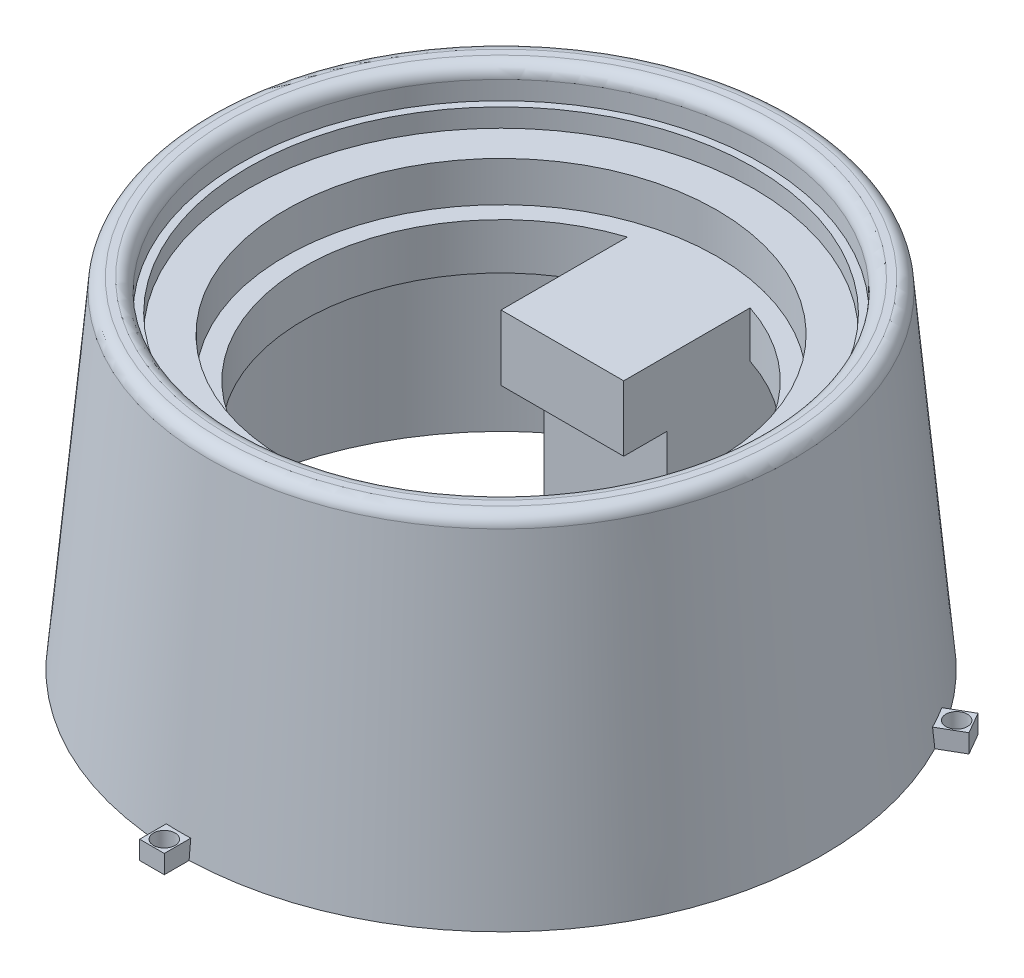
SolidWorks part; units mm, degrees
ref_plane "前视基准面" through (0, 0, 0) normal (0, 0, 1) x (1, 0, 0)
ref_plane "上视基准面" through (0, 0, 0) normal (0, 1, 0) x (1, 0, 0)
ref_plane "右视基准面" through (0, 0, 0) normal (1, 0, 0) x (0, 0, -1)
other "Configuration Table"
sketch "草图1" plane through (0, 0, 0) normal (0, 1, 0) x (1, 0, 0)
  circle A0 centre (0, 0) radius 52.22
  circle A1 centre (0, 0) radius 47.22
  circle A2 centre (0, 0) radius 42.22
  dimension "D1" = 104.44
  dimension "D2" = 94.44
  dimension "D3" = 84.44
extrude "凸台-拉伸1" add sketch "草图1" along normal blind 50 contours A2 | A0 A1 | A1 A2
sketch "草图3" plane through (0, 50, 0) normal (0, 1, 0) x (1, 0, 0)
  circle A1 centre (0, 0) radius 52.22
  circle A2 centre (0, 0) radius 52.22
  circle A3 centre (0, 0) radius 42.22
  circle A4 centre (0, 0) radius 42.22
  circle A5 centre (0, 0) radius 47.22
  circle A6 centre (0, 0) radius 47.22
  circle A7 centre (0, 0) radius 52.22
  circle A8 centre (0, 0) radius 52.22
  circle M5 centre (0, 0) radius 52.22
  dimension "D5" = 94.44
  dimension "D6" = 84.44
  dimension "D1" = 0
  dimension "D2" = 0
  dimension "D3" = 0
  dimension "D4" = 0
extrude "凸台-拉伸2" add sketch "草图3" along normal blind 5 contours A6 M5 | A6 A4
sketch "草图5" plane through (0, 0, 0) normal (1, 0, 0) x (0, 0, -1)
  line L0 (52.22, 55) -> (52.22, 0)
  line L1 (55, 0) -> (-55, 0) construction
  line L2 (52.22, 0) -> (52.22, 55) construction
  line L3 (52.22, 0) -> (47.22, 55)
  line L4 (52.22, 55) -> (-52.22, 55) construction
  line L5 (47.22, 55) -> (52.22, 55)
  line L6 (0, 58.8576) -> (0, -9.8994) construction
revolve "切除-旋转2" cut sketch "草图5" angle 360 about L6
sketch "草图6" plane through (0, 50, 0) normal (0, 1, 0) x (1, 0, 0)
  line L0 (9.95, 9.95) -> (9.95, -30.45)
  line L2 (9.95, 9.95) -> (-9.95, 9.95)
  line L3 (-9.95, 9.95) -> (-9.95, -30.45)
  line L4 (-9.95, -30.45) -> (9.95, -30.45)
extrude "切除-拉伸1" cut sketch "草图6" against normal up to next
sketch "草图8" plane through (0, 50, 0) normal (0, 1, 0) x (1, 0, 0)
  line L0 (-9.95, 9.95) -> (-9.95, 16.95)
  line L1 (9.95, 9.95) -> (9.95, 16.95)
  line L2 (9.95, 16.95) -> (-9.95, 16.95)
  line L3 (-9.95, -30.45) -> (-9.95, -37.45)
  line L4 (9.95, -30.45) -> (9.95, -37.45)
  line L5 (9.95, -37.45) -> (-9.95, -37.45)
  line L6 (-9.95, 9.95) -> (9.95, 9.95)
  line L7 (-9.95, -30.45) -> (9.95, -30.45)
sketch "草图9" plane through (0, 0, 0) normal (0, -1, 0) x (1, 0, 0)
  line L4 (-9.95, 37.45) -> (-9.95, 30.45)
  line L5 (9.95, 37.45) -> (-9.95, 37.45)
  line L6 (9.95, 30.45) -> (9.95, 37.45)
  line L7 (-9.95, 30.45) -> (9.95, 30.45)
  line L8 (-9.95, 37.45) -> (-9.95, 30.45)
  line L9 (9.95, 37.45) -> (-9.95, 37.45)
  line L10 (9.95, 30.45) -> (9.95, 37.45)
  line L11 (-9.95, 30.45) -> (9.95, 30.45)
  line L12 (-9.95, -9.95) -> (-9.95, -16.95)
  line L13 (-9.95, -16.95) -> (9.95, -16.95)
  line L14 (9.95, -16.95) -> (9.95, -9.95)
  line L15 (9.95, -9.95) -> (-9.95, -9.95)
  line L16 (-9.95, -9.95) -> (-9.95, -16.95)
  line L17 (-9.95, -16.95) -> (9.95, -16.95)
  line L18 (9.95, -16.95) -> (9.95, -9.95)
  line L19 (9.95, -9.95) -> (-9.95, -9.95)
  dimension "D1" = 0
  dimension "D2" = 0
extrude "切除-拉伸2" cut sketch "草图9" against normal blind 29.9
sketch "草图10" plane through (0, 29.9, 0) normal (0, -1, 0) x (1, 0, 0)
  line L0 (9.95, 37.45) -> (4.95, 37.45)
  line L1 (9.95, 37.45) -> (-9.95, 37.45) construction
  line L2 (4.95, 37.45) -> (4.95, 34.55)
  line L3 (-9.95, 37.45) -> (-4.95, 37.45)
  line L4 (-4.95, 37.45) -> (-4.95, 34.55)
  line L5 (-9.95, -16.95) -> (-4.95, -16.95)
  line L6 (9.95, -16.95) -> (-9.95, -16.95) construction
  line L7 (-4.95, -16.95) -> (-4.95, -14.05)
  line L8 (9.95, -16.95) -> (4.95, -16.95)
  line L9 (4.95, -16.95) -> (4.95, -14.05)
  circle A0 centre (4.95, 34.55) radius 1.75
  circle A1 centre (-4.95, 34.55) radius 1.75
  circle A2 centre (-4.95, -14.05) radius 1.75
  circle A3 centre (4.95, -14.05) radius 1.75
sketch "草图13" plane through (0, 0, 0) normal (0, 0, 1) x (1, 0, 0)
  line L1 (-5, 0) -> (5, 0)
  line L2 (-52.22, 0) -> (52.22, 0) construction
  line L3 (-5, 0) -> (-5, 10)
  line L4 (-5, 10) -> (5, 10)
  line L5 (5, 10) -> (5, 0)
extrude "切除-拉伸3" cut sketch "草图13" against normal through all
sketch "草图14" plane through (0, 50, 0) normal (0, 1, 0) x (1, 0, 0)
  line L0 (-9.95, -30.45) -> (9.95, -30.45)
  line L1 (9.95, -30.45) -> (9.95, 9.95)
  line L2 (9.95, 9.95) -> (-9.95, 9.95)
  line L3 (-9.95, 9.95) -> (-9.95, -30.45)
  circle A1 centre (0, 0) radius 35
  circle A2 centre (0, 0) radius 42.22
  circle A3 centre (0, 0) radius 42.22
  circle A4 centre (0, 0) radius 41
  dimension "D1" = 0
  dimension "D2" = 84.44
  dimension "D3" = 32.0344
extrude "切除-拉伸4" cut sketch "草图14" against normal blind 3 contours A4 A1
sketch "草图15" plane through (0, 50, 0) normal (0, 1, 0) x (1, 0, 0)
  line L0 (-9.95, 9.95) -> (-9.95, 30.45)
  line L1 (-9.95, 30.45) -> (9.95, 30.45)
  line L2 (9.95, 30.45) -> (9.95, 9.95)
  line L4 (-9.95, -30.45) -> (9.95, -30.45)
  line L5 (9.95, -30.45) -> (9.95, 9.95)
  line L6 (9.95, 9.95) -> (-9.95, 9.95)
  line L7 (-9.95, 9.95) -> (-9.95, -30.45)
  line L8 (-9.95, -30.45) -> (9.95, -30.45)
  line L9 (9.95, -30.45) -> (9.95, 9.95)
  line L10 (9.95, 9.95) -> (-9.95, 9.95)
  line L11 (-9.95, 9.95) -> (-9.95, -30.45)
  circle A0 centre (0, 0) radius 32.0344
  circle A1 centre (0, 0) radius 35
  circle A2 centre (0, 0) radius 35
  circle A3 centre (0, 0) radius 41
  circle A4 centre (0, 0) radius 41
  circle A5 centre (0, 0) radius 42.22
  circle A6 centre (0, 0) radius 42.22
  circle A7 centre (0, 0) radius 35
  circle A8 centre (0, 0) radius 35
  line M11 (9.95, 9.95) -> (9.95, -30.45)
  line M13 (-9.95, -30.45) -> (-9.95, 9.95)
  dimension "D1" = 0
  dimension "D2" = 0
  dimension "D3" = 0
  dimension "D4" = 0
  dimension "D5" = 0
extrude "切除-拉伸5" cut sketch "草图15" against normal through all contours L0 A0 M13 | A0 L2 M11
sketch "草图17" plane through (0, 0, 0) normal (0, -1, 0) x (1, 0, 0)
  line L0 (-9.95, -16.95) -> (-9.95, 46.1598)
  line L1 (-9.95, -16.95) -> (-9.95, -46.1598)
  line L2 (9.95, 37.45) -> (9.95, -46.1598)
  line L3 (9.95, 37.45) -> (9.95, 46.1598)
  circle A1 centre (0, 0) radius 42.22
  circle A2 centre (0, 0) radius 42.22
  circle A3 centre (0, 0) radius 47.22
  circle A4 centre (0, 0) radius 47.22
  circle A5 centre (0, 0) radius 52.22
  circle A6 centre (0, 0) radius 52.22
  arc M6 (-9.95, -30.45) -> (-9.95, 30.45) centre (0, 0) cw
  line M7 (-9.95, 30.45) -> (-9.95, 37.45)
  line M9 (9.95, 37.45) -> (9.95, 30.45)
  arc M10 (9.95, 30.45) -> (9.95, -30.45) centre (0, 0) cw
  dimension "D1" = 0
  dimension "D2" = 0
  dimension "D3" = 0
extrude "切除-拉伸6" cut sketch "草图17" against normal blind 33 contours L0 A2 L1 M6 M7 | L0 A4 L1 A2 | L2 A2 L3 M9 M10 | L2 A4 L3 A2
sketch "草图20" plane through (0, 0, -9.95) normal (0, 0, 1) x (1, 0, 0)
  line L0 (-9.95, 29.9) -> (-9.95, 40.5)
  line L1 (-9.95, 29.9) -> (-4.95, 29.9) construction
  line L2 (-9.95, 40.5) -> (-9.95, 50)
  line L3 (9.95, 50) -> (-9.95, 50) construction
sketch "草图21" plane through (0, 50, 0) normal (0, 1, 0) x (1, 0, 0)
  circle A1 centre (0, 0) radius 35
  circle A2 centre (0, 0) radius 35
  dimension "D1" = 0
extrude "切除-拉伸7" cut sketch "草图21" against normal blind 9.5
sketch "草图22" plane through (0, 0, 0) normal (0, -1, 0) x (1, 0, 0)
  line L0 (0, 0) -> (-0.4162, 52.2183)
  line L1 (0, 0) -> (45.4305, -25.7487)
  line L2 (0, 0) -> (-45.0143, -26.4696)
  line L3 (-0.4162, 52.2183) -> (-0.4162, 56.2183)
  line L4 (-0.4162, 56.2183) -> (-2.4162, 56.2183)
  line L5 (-0.4162, 56.2183) -> (1.5838, 56.2183)
  line L6 (-2.4162, 56.2183) -> (-2.4162, 50.2183)
  line L7 (-2.4162, 50.2183) -> (1.5838, 50.2183)
  line L8 (1.5838, 50.2183) -> (1.5838, 56.2183)
  line L9 (-9.95, 46.1598) -> (-9.95, 37.45)
  line L10 (-9.95, 37.45) -> (9.95, 37.45)
  line L11 (9.95, 37.45) -> (9.95, 46.1598)
  line L12 (9.95, -46.1598) -> (9.95, -16.95)
  line L13 (9.95, -16.95) -> (5, -16.95)
  line L14 (5, -16.95) -> (5, -51.9801)
  line L15 (-5, -51.9801) -> (-5, -16.95)
  line L16 (-5, -16.95) -> (-9.95, -16.95)
  line L17 (-9.95, -16.95) -> (-9.95, -46.1598)
  line L18 (-9.95, 46.1598) -> (-9.95, 37.45)
  line L19 (-9.95, 37.45) -> (9.95, 37.45)
  line L20 (9.95, 37.45) -> (9.95, 46.1598)
  line L21 (9.95, -46.1598) -> (9.95, -16.95)
  line L22 (9.95, -16.95) -> (5, -16.95)
  line L23 (5, -16.95) -> (5, -51.9801)
  line L24 (-5, -51.9801) -> (-5, -16.95)
  line L25 (-5, -16.95) -> (-9.95, -16.95)
  line L26 (-9.95, -16.95) -> (-9.95, -46.1598)
  line L27 (48.8946, -27.7487) -> (49.8946, -26.0167)
  line L28 (48.8946, -27.7487) -> (47.8946, -29.4808)
  line L29 (49.8946, -26.0167) -> (44.6985, -23.0167)
  line L30 (45.4305, -25.7487) -> (48.8946, -27.7487)
  line L31 (42.6985, -26.4808) -> (47.8946, -29.4808)
  line L32 (44.6985, -23.0167) -> (42.6985, -26.4808)
  line L33 (-48.4784, -28.4696) -> (-47.4784, -30.2017)
  line L34 (-48.4784, -28.4696) -> (-49.4784, -26.7376)
  line L35 (-47.4784, -30.2017) -> (-42.2823, -27.2017)
  line L36 (-45.0143, -26.4696) -> (-48.4784, -28.4696)
  line L37 (-44.2823, -23.7376) -> (-49.4784, -26.7376)
  line L38 (-42.2823, -27.2017) -> (-44.2823, -23.7376)
  circle A0 centre (-0.4162, 54.2183) radius 1.75
  circle A1 centre (47.1626, -26.7487) radius 1.75
  circle A2 centre (-46.7464, -27.4696) radius 1.75
  arc A3 (-9.95, 46.1598) -> (-9.95, -46.1598) centre (0, 0) ccw
  arc A4 (9.95, -46.1598) -> (9.95, 46.1598) centre (0, 0) ccw
  arc A5 (5, -51.9801) -> (-5, -51.9801) centre (0, 0) ccw
  arc A6 (-9.95, 46.1598) -> (-9.95, -46.1598) centre (0, 0) ccw
  arc A7 (9.95, -46.1598) -> (9.95, 46.1598) centre (0, 0) ccw
  arc A8 (5, -51.9801) -> (-5, -51.9801) centre (0, 0) ccw
  point P43 (0, 0)
  arc M26 (5, -51.9801) -> (-5, -51.9801) centre (0, 0) ccw
  dimension "D4" = 3
  dimension "D2" = 120
  dimension "D3" = 120
  dimension "D1" = 0
extrude "凸台-拉伸3" add sketch "草图22" against normal blind 3 contours A0 L3 L4 L6 M26 | A0 L3 L8 L5 M26 | L7 L8 L0 M26 | L6 L7 L0 M26 | A1 L30 L27 L29 M26 | L29 L32 L1 M26 | L1 L32 L31 M26 | A1 L30 L31 L28 M26 | A2 L36 L37 L34 M26 | L2 L38 L37 M26 | L35 L38 L2 M26 | A2 L36 L33 L35 M26
extrude "切除-拉伸8" cut sketch "草图10" against normal blind 10
fillet "圆角1" radius 2 1 edges at (0, 55, 47.22)
fillet "圆角2" radius 2 1 edges at (0, 55, 42.22)
